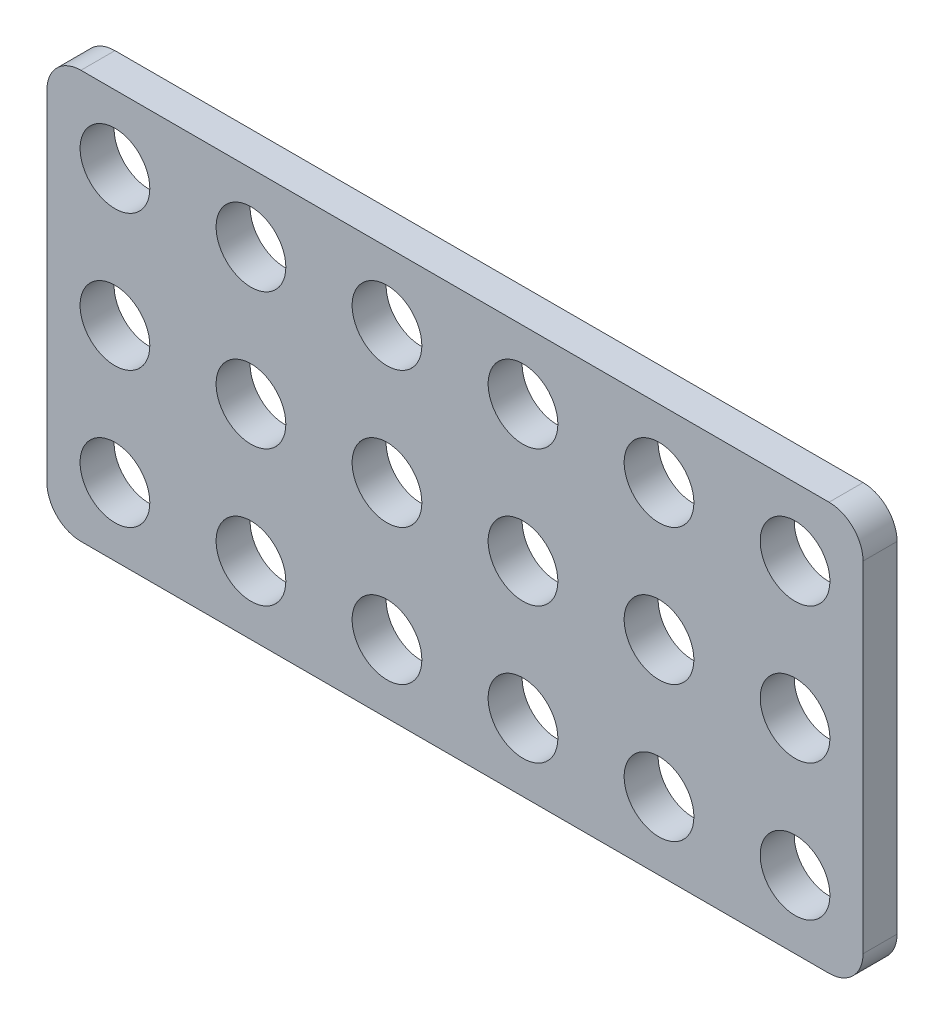
SolidWorks part; units mm, degrees
ref_plane "Front Plane" through (0, 0, 0) normal (0, 0, 1) x (1, 0, 0)
ref_plane "Top Plane" through (0, 0, 0) normal (0, 1, 0) x (1, 0, 0)
ref_plane "Right Plane" through (0, 0, 0) normal (1, 0, 0) x (0, 0, -1)
sketch "Sketch1" plane through (0, 0, 0) normal (0, 0, 1) x (1, 0, 0)
  line L1 (0, 0) -> (48, 0)
  line L2 (0, 0) -> (0, 24)
  line L3 (0, 24) -> (48, 24)
  line L4 (48, 0) -> (48, 24)
  dimension "D1" = 48
  dimension "D2" = 24
extrude "Boss-Extrude1" add sketch "Sketch1" along normal blind 2
sketch "Sketch2" plane through (0, 0, 2) normal (0, 0, 1) x (1, 0, 0)
  line L0 (48, 24) -> (0, 24) construction
  line L1 (0, 24) -> (0, 0) construction
  circle A0 centre (4, 20) radius 2.05
  dimension "D1" = 4.1
  dimension "D2" = 4
  dimension "D3" = 4
extrude "Cut-Extrude1" cut sketch "Sketch2" against normal through all
pattern_linear "LPattern1" count 6 spacing 8 along (1, 0, 0) count 3 spacing 8 along (0, -1, 0) of "Cut-Extrude1"
fillet "Fillet1" radius 2 4 edges at (0, 0, 1) (48, 0, 1) (48, 24, 1) (0, 24, 1)
